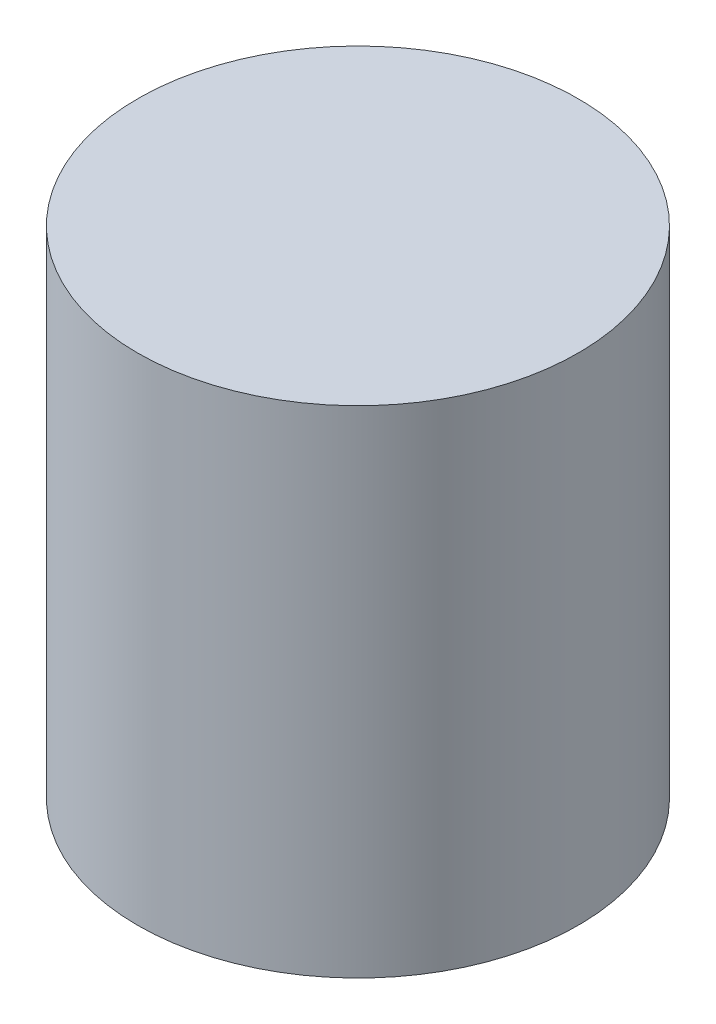
SolidWorks part; units mm, degrees
ref_plane "Front Plane" through (0, 0, 0) normal (0, 0, 1) x (1, 0, 0)
ref_plane "Top Plane" through (0, 0, 0) normal (0, 1, 0) x (1, 0, 0)
ref_plane "Right Plane" through (0, 0, 0) normal (1, 0, 0) x (0, 0, -1)
sketch "Sketch1" plane through (0, 0, 0) normal (0, 1, 0) x (1, 0, 0)
  circle A0 centre (0, 0) radius 4
  dimension "D1" = 8
extrude "Boss-Extrude1" add sketch "Sketch1" along normal blind 9
